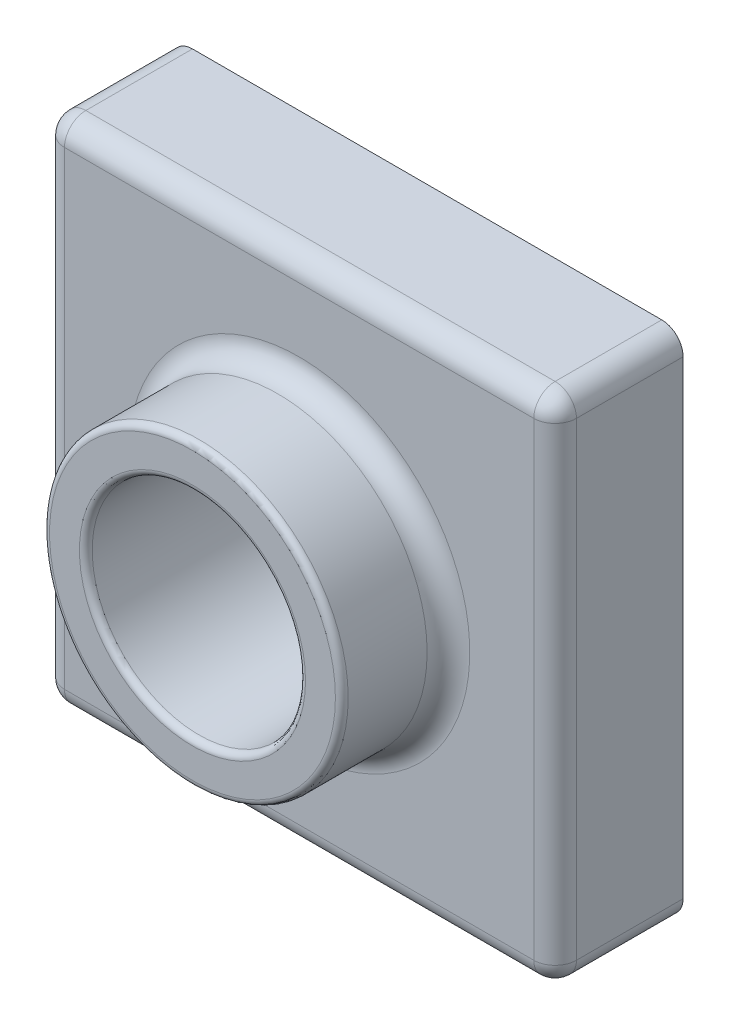
SolidWorks part; units mm, degrees
ref_plane "Front Plane" through (0, 0, 0) normal (0, 0, 1) x (1, 0, 0)
ref_plane "Top Plane" through (0, 0, 0) normal (0, 1, 0) x (1, 0, 0)
ref_plane "Right Plane" through (0, 0, 0) normal (1, 0, 0) x (0, 0, -1)
other "Configuration Table"
sketch "Sketch2" plane through (0, 0, 0) normal (0, 0, 1) x (1, 0, 0)
  line L1 (0, 0) -> (120, 0)
  line L2 (0, 0) -> (0, 120)
  line L3 (0, 120) -> (120, 120)
  line L4 (120, 0) -> (120, 120)
  dimension "D1" = 120
  dimension "D2" = 120
extrude "Boss-Extrude1" add sketch "Sketch2" along normal blind 30
sketch "Sketch4" plane through (0, 0, 30) normal (0, 0, 1) x (1, 0, 0)
  line L0 (120, 120) -> (0, 120) construction
  line L1 (0, 120) -> (0, 0) construction
  circle A0 centre (60, 60) radius 35
  dimension "D1" = 60
  dimension "D3" = 70
  dimension "D2" = 60
extrude "Boss-Extrude2" add sketch "Sketch4" along normal blind 25
sketch "Sketch6" plane through (0, 0, 55) normal (0, 0, 1) x (1, 0, 0)
  circle A0 centre (60, 60) radius 25
  dimension "D1" = 50
extrude "Cut-Extrude1" cut sketch "Sketch6" against normal through all
fillet "Fillet1" radius 5 9 edges at (25, 60, 30) (60, 120, 30) (120, 60, 30) (60, 0, 30) (0, 60, 30) (0, 0, 15) (120, 0, 15) (120, 120, 15) (0, 120, 15)
fillet "Fillet2" radius 1.5 2 edges at (95, 60, 55) (85, 60, 55)
shell "Shell1" thickness 2
